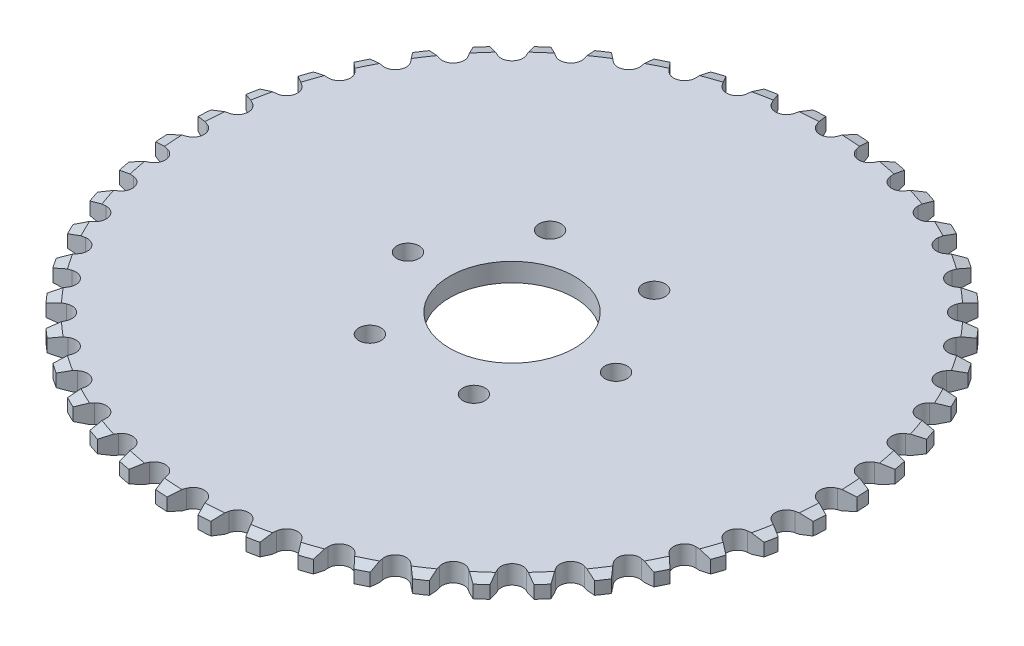
SolidWorks part; units mm, degrees
material "Cast Alloy Steel"
ref_plane "Front Plane" through (0, 0, 0) normal (0, 0, 1) x (1, 0, 0)
ref_plane "Top Plane" through (0, 0, 0) normal (0, 1, 0) x (1, 0, 0)
ref_plane "Right Plane" through (0, 0, 0) normal (1, 0, 0) x (0, 0, -1)
sketch "Sketch1" plane through (0, 0, 0) normal (0, 1, 0) x (1, 0, 0)
  circle A0 centre (0, 0) radius 75.5015
  circle A1 centre (0, 0) radius 14.2812
  dimension "D1" = 151.003
  dimension "D2" = 28.5623
extrude "Boss-Extrude1" add sketch "Sketch1" along normal blind 4.2672
sketch "Sketch2" plane through (0, 4.2672, 0) normal (0, 1, 0) x (1, 0, 0)
  circle A0 centre (0, 0) radius 23.8125 construction
  circle A1 centre (-23.8125, 0) radius 2.54
  circle A2 centre (-11.9063, 20.6222) radius 2.54
  circle A3 centre (11.9062, 20.6222) radius 2.54
  circle A4 centre (23.8125, 0) radius 2.54
  circle A5 centre (11.9063, -20.6222) radius 2.54
  circle A6 centre (-11.9062, -20.6222) radius 2.54
  point P18 (0, 0)
  dimension "D1" = 47.625
  dimension "D2" = 5.08
  dimension "D3" = 6
extrude "Cut-Extrude1" cut sketch "Sketch2" against normal through all
chamfer "Chamfer1" distance 2.54 angle 15 2 edges at (0, 0, 75.5015) (0, 4.2672, 75.5015)
sketch "Sketch3" plane through (0, 4.2672, 0) normal (0, 1, 0) x (1, 0, 0)
  line L0 (0, 75.5015) -> (0, -75.5015) construction
  line L1 (2.363, 72.1269) -> (3.5606, 75.4175)
  line L2 (-2.363, 72.1269) -> (-3.5606, 75.4175)
  line L3 (7.0717, 71.8182) -> (6.3138, 75.237)
  line L4 (11.7572, 71.2014) -> (13.3741, 74.3075)
  line L5 (16.3854, 70.2808) -> (16.0802, 73.7693)
  line L6 (20.9502, 69.0576) -> (22.9588, 71.9261)
  line L7 (25.4187, 67.5408) -> (25.5714, 71.0393)
  line L8 (29.7848, 65.7323) -> (32.1506, 68.3141)
  line L9 (34.0171, 63.6452) -> (34.6251, 67.0938)
  line L10 (38.1098, 61.2822) -> (40.7924, 63.5331)
  line L11 (42.0334, 58.6606) -> (43.0864, 62.0003)
  line L12 (45.7827, 55.7836) -> (48.7361, 57.6651)
  line L13 (49.3305, 52.6722) -> (50.8105, 55.846)
  line L14 (52.6722, 49.3305) -> (55.846, 50.8105)
  line L15 (55.7836, 45.7827) -> (57.6651, 48.7361)
  line L16 (58.6606, 42.0334) -> (62.0003, 43.0864)
  line L17 (61.2822, 38.1098) -> (63.5331, 40.7924)
  line L18 (63.6452, 34.0171) -> (67.0938, 34.6251)
  line L19 (65.7323, 29.7848) -> (68.3141, 32.1506)
  line L20 (67.5408, 25.4187) -> (71.0393, 25.5714)
  line L21 (69.0576, 20.9502) -> (71.9261, 22.9588)
  line L22 (70.2808, 16.3854) -> (73.7693, 16.0802)
  line L23 (71.2014, 11.7572) -> (74.3075, 13.3741)
  line L24 (71.8182, 7.0717) -> (75.237, 6.3138)
  line L25 (72.1269, 2.363) -> (75.4175, 3.5606)
  line L26 (72.1269, -2.363) -> (75.4175, -3.5606)
  line L27 (71.8182, -7.0717) -> (75.237, -6.3138)
  line L28 (71.2014, -11.7572) -> (74.3075, -13.3741)
  line L29 (70.2808, -16.3854) -> (73.7693, -16.0802)
  line L30 (69.0576, -20.9502) -> (71.9261, -22.9588)
  line L31 (67.5408, -25.4187) -> (71.0393, -25.5714)
  line L32 (65.7323, -29.7848) -> (68.3141, -32.1506)
  line L33 (63.6452, -34.0171) -> (67.0938, -34.6251)
  line L34 (61.2822, -38.1098) -> (63.5331, -40.7924)
  line L35 (58.6606, -42.0334) -> (62.0003, -43.0864)
  line L36 (55.7836, -45.7827) -> (57.6651, -48.7361)
  line L37 (52.6722, -49.3305) -> (55.846, -50.8105)
  line L38 (49.3305, -52.6722) -> (50.8105, -55.846)
  line L39 (45.7827, -55.7836) -> (48.7361, -57.6651)
  line L40 (42.0334, -58.6606) -> (43.0864, -62.0003)
  line L41 (38.1098, -61.2822) -> (40.7924, -63.5331)
  line L42 (34.0171, -63.6452) -> (34.6251, -67.0938)
  line L43 (29.7848, -65.7323) -> (32.1506, -68.3141)
  line L44 (25.4187, -67.5408) -> (25.5714, -71.0393)
  line L45 (20.9502, -69.0576) -> (22.9588, -71.9261)
  line L46 (16.3854, -70.2808) -> (16.0802, -73.7693)
  line L47 (11.7572, -71.2014) -> (13.3741, -74.3075)
  line L48 (7.0717, -71.8182) -> (6.3138, -75.237)
  line L49 (2.363, -72.1269) -> (3.5606, -75.4175)
  line L50 (-2.363, -72.1269) -> (-3.5606, -75.4175)
  line L51 (-7.0717, -71.8182) -> (-6.3138, -75.237)
  line L52 (-11.7572, -71.2014) -> (-13.3741, -74.3075)
  line L53 (-16.3854, -70.2808) -> (-16.0802, -73.7693)
  line L54 (-20.9502, -69.0576) -> (-22.9588, -71.9261)
  line L55 (-25.4187, -67.5408) -> (-25.5714, -71.0393)
  line L56 (-29.7848, -65.7323) -> (-32.1506, -68.3141)
  line L57 (-34.0171, -63.6452) -> (-34.6251, -67.0938)
  line L58 (-38.1098, -61.2822) -> (-40.7924, -63.5331)
  line L59 (-42.0334, -58.6606) -> (-43.0864, -62.0003)
  line L60 (-45.7827, -55.7836) -> (-48.7361, -57.6651)
  line L61 (-49.3305, -52.6722) -> (-50.8105, -55.846)
  line L62 (-52.6722, -49.3305) -> (-55.846, -50.8105)
  line L63 (-55.7836, -45.7827) -> (-57.6651, -48.7361)
  line L64 (-58.6606, -42.0334) -> (-62.0003, -43.0864)
  line L65 (-61.2822, -38.1098) -> (-63.5331, -40.7924)
  line L66 (-63.6452, -34.0171) -> (-67.0938, -34.6251)
  line L67 (-65.7323, -29.7848) -> (-68.3141, -32.1506)
  line L68 (-67.5408, -25.4187) -> (-71.0393, -25.5714)
  line L69 (-69.0576, -20.9502) -> (-71.9261, -22.9588)
  line L70 (-70.2808, -16.3854) -> (-73.7693, -16.0802)
  line L71 (-71.2014, -11.7572) -> (-74.3075, -13.3741)
  line L72 (-71.8182, -7.0717) -> (-75.237, -6.3138)
  line L73 (-72.1269, -2.363) -> (-75.4175, -3.5606)
  line L74 (-72.1269, 2.363) -> (-75.4175, 3.5606)
  line L75 (-71.8182, 7.0717) -> (-75.237, 6.3138)
  line L76 (-71.2014, 11.7572) -> (-74.3075, 13.3741)
  line L77 (-70.2808, 16.3854) -> (-73.7693, 16.0802)
  line L78 (-69.0576, 20.9502) -> (-71.9261, 22.9588)
  line L79 (-67.5408, 25.4187) -> (-71.0393, 25.5714)
  line L80 (-65.7323, 29.7848) -> (-68.3141, 32.1506)
  line L81 (-63.6452, 34.0171) -> (-67.0938, 34.6251)
  line L82 (-61.2822, 38.1098) -> (-63.5331, 40.7924)
  line L83 (-58.6606, 42.0334) -> (-62.0003, 43.0864)
  line L84 (-55.7836, 45.7827) -> (-57.6651, 48.7361)
  line L85 (-52.6722, 49.3305) -> (-55.846, 50.8105)
  line L86 (-49.3305, 52.6722) -> (-50.8105, 55.846)
  line L87 (-45.7827, 55.7836) -> (-48.7361, 57.6651)
  line L88 (-42.0334, 58.6606) -> (-43.0864, 62.0003)
  line L89 (-38.1098, 61.2822) -> (-40.7924, 63.5331)
  line L90 (-34.0171, 63.6452) -> (-34.6251, 67.0938)
  line L91 (-29.7848, 65.7323) -> (-32.1506, 68.3141)
  line L92 (-25.4187, 67.5408) -> (-25.5714, 71.0393)
  line L93 (-20.9502, 69.0576) -> (-22.9588, 71.9261)
  line L94 (-16.3854, 70.2808) -> (-16.0802, 73.7693)
  line L95 (-11.7572, 71.2014) -> (-13.3741, 74.3075)
  line L96 (-7.0717, 71.8182) -> (-6.3138, 75.237)
  circle A0 centre (0, 0) radius 72.9869 construction
  circle A1 centre (0, 0) radius 75.5015 construction
  arc A2 (-2.363, 72.1269) -> (2.363, 72.1269) centre (0, 72.9869) ccw
  arc A3 (3.5606, 75.4175) -> (-3.5606, 75.4175) centre (0, 0) ccw
  arc A4 (7.0717, 71.8182) -> (11.7572, 71.2014) centre (9.5267, 72.3625) ccw
  arc A5 (13.3741, 74.3075) -> (6.3138, 75.237) centre (0, 0) ccw
  arc A6 (16.3854, 70.2808) -> (20.9502, 69.0576) centre (18.8904, 70.4999) ccw
  arc A7 (22.9588, 71.9261) -> (16.0802, 73.7693) centre (0, 0) ccw
  arc A8 (25.4187, 67.5408) -> (29.7848, 65.7323) centre (27.9309, 67.4311) ccw
  arc A9 (32.1506, 68.3141) -> (25.5714, 71.0393) centre (0, 0) ccw
  arc A10 (34.0171, 63.6452) -> (38.1098, 61.2822) centre (36.4934, 63.2085) ccw
  arc A11 (40.7924, 63.5331) -> (34.6251, 67.0938) centre (0, 0) ccw
  arc A12 (42.0334, 58.6606) -> (45.7827, 55.7836) centre (44.4316, 57.9044) ccw
  arc A13 (48.7361, 57.6651) -> (43.0864, 62.0003) centre (0, 0) ccw
  arc A14 (49.3305, 52.6722) -> (52.6722, 49.3305) centre (51.6095, 51.6095) ccw
  arc A15 (55.846, 50.8105) -> (50.8105, 55.846) centre (0, 0) ccw
  arc A16 (55.7836, 45.7827) -> (58.6606, 42.0334) centre (57.9044, 44.4316) ccw
  arc A17 (62.0003, 43.0864) -> (57.6651, 48.7361) centre (0, 0) ccw
  arc A18 (61.2822, 38.1098) -> (63.6452, 34.0171) centre (63.2085, 36.4935) ccw
  arc A19 (67.0938, 34.6251) -> (63.5331, 40.7924) centre (0, 0) ccw
  arc A20 (65.7323, 29.7848) -> (67.5408, 25.4187) centre (67.4311, 27.9309) ccw
  arc A21 (71.0393, 25.5714) -> (68.3141, 32.1506) centre (0, 0) ccw
  arc A22 (69.0576, 20.9502) -> (70.2808, 16.3854) centre (70.4999, 18.8904) ccw
  arc A23 (73.7693, 16.0802) -> (71.9261, 22.9588) centre (0, 0) ccw
  arc A24 (71.2014, 11.7572) -> (71.8182, 7.0717) centre (72.3625, 9.5267) ccw
  arc A25 (75.237, 6.3138) -> (74.3075, 13.3741) centre (0, 0) ccw
  arc A26 (72.1269, 2.363) -> (72.1269, -2.363) centre (72.9869, 0) ccw
  arc A27 (75.4175, -3.5606) -> (75.4175, 3.5606) centre (0, 0) ccw
  arc A28 (71.8182, -7.0717) -> (71.2014, -11.7572) centre (72.3625, -9.5267) ccw
  arc A29 (74.3075, -13.3741) -> (75.237, -6.3138) centre (0, 0) ccw
  arc A30 (70.2808, -16.3854) -> (69.0576, -20.9502) centre (70.4999, -18.8904) ccw
  arc A31 (71.9261, -22.9588) -> (73.7693, -16.0802) centre (0, 0) ccw
  arc A32 (67.5408, -25.4187) -> (65.7323, -29.7848) centre (67.4311, -27.9309) ccw
  arc A33 (68.3141, -32.1506) -> (71.0393, -25.5714) centre (0, 0) ccw
  arc A34 (63.6452, -34.0171) -> (61.2822, -38.1098) centre (63.2085, -36.4934) ccw
  arc A35 (63.5331, -40.7924) -> (67.0938, -34.6251) centre (0, 0) ccw
  arc A36 (58.6606, -42.0334) -> (55.7836, -45.7827) centre (57.9044, -44.4316) ccw
  arc A37 (57.6651, -48.7361) -> (62.0003, -43.0864) centre (0, 0) ccw
  arc A38 (52.6722, -49.3305) -> (49.3305, -52.6722) centre (51.6095, -51.6095) ccw
  arc A39 (50.8105, -55.846) -> (55.846, -50.8105) centre (0, 0) ccw
  arc A40 (45.7827, -55.7836) -> (42.0334, -58.6606) centre (44.4316, -57.9044) ccw
  arc A41 (43.0864, -62.0003) -> (48.7361, -57.6651) centre (0, 0) ccw
  arc A42 (38.1098, -61.2822) -> (34.0171, -63.6452) centre (36.4935, -63.2085) ccw
  arc A43 (34.6251, -67.0938) -> (40.7924, -63.5331) centre (0, 0) ccw
  arc A44 (29.7848, -65.7323) -> (25.4187, -67.5408) centre (27.9309, -67.4311) ccw
  arc A45 (25.5714, -71.0393) -> (32.1506, -68.3141) centre (0, 0) ccw
  arc A46 (20.9502, -69.0576) -> (16.3854, -70.2808) centre (18.8904, -70.4999) ccw
  arc A47 (16.0802, -73.7693) -> (22.9588, -71.9261) centre (0, 0) ccw
  arc A48 (11.7572, -71.2014) -> (7.0717, -71.8182) centre (9.5267, -72.3625) ccw
  arc A49 (6.3138, -75.237) -> (13.3741, -74.3075) centre (0, 0) ccw
  arc A50 (2.363, -72.1269) -> (-2.363, -72.1269) centre (0, -72.9869) ccw
  arc A51 (-3.5606, -75.4175) -> (3.5606, -75.4175) centre (0, 0) ccw
  arc A52 (-7.0717, -71.8182) -> (-11.7572, -71.2014) centre (-9.5267, -72.3625) ccw
  arc A53 (-13.3741, -74.3075) -> (-6.3138, -75.237) centre (0, 0) ccw
  arc A54 (-16.3854, -70.2808) -> (-20.9502, -69.0576) centre (-18.8904, -70.4999) ccw
  arc A55 (-22.9588, -71.9261) -> (-16.0802, -73.7693) centre (0, 0) ccw
  arc A56 (-25.4187, -67.5408) -> (-29.7848, -65.7323) centre (-27.9309, -67.4311) ccw
  arc A57 (-32.1506, -68.3141) -> (-25.5714, -71.0393) centre (0, 0) ccw
  arc A58 (-34.0171, -63.6452) -> (-38.1098, -61.2822) centre (-36.4934, -63.2085) ccw
  arc A59 (-40.7924, -63.5331) -> (-34.6251, -67.0938) centre (0, 0) ccw
  arc A60 (-42.0334, -58.6606) -> (-45.7827, -55.7836) centre (-44.4316, -57.9044) ccw
  arc A61 (-48.7361, -57.6651) -> (-43.0864, -62.0003) centre (0, 0) ccw
  arc A62 (-49.3305, -52.6722) -> (-52.6722, -49.3305) centre (-51.6095, -51.6095) ccw
  arc A63 (-55.846, -50.8105) -> (-50.8105, -55.846) centre (0, 0) ccw
  arc A64 (-55.7836, -45.7827) -> (-58.6606, -42.0334) centre (-57.9044, -44.4316) ccw
  arc A65 (-62.0003, -43.0864) -> (-57.6651, -48.7361) centre (0, 0) ccw
  arc A66 (-61.2822, -38.1098) -> (-63.6452, -34.0171) centre (-63.2085, -36.4935) ccw
  arc A67 (-67.0938, -34.6251) -> (-63.5331, -40.7924) centre (0, 0) ccw
  arc A68 (-65.7323, -29.7848) -> (-67.5408, -25.4187) centre (-67.4311, -27.9309) ccw
  arc A69 (-71.0393, -25.5714) -> (-68.3141, -32.1506) centre (0, 0) ccw
  arc A70 (-69.0576, -20.9502) -> (-70.2808, -16.3854) centre (-70.4999, -18.8904) ccw
  arc A71 (-73.7693, -16.0802) -> (-71.9261, -22.9588) centre (0, 0) ccw
  arc A72 (-71.2014, -11.7572) -> (-71.8182, -7.0717) centre (-72.3625, -9.5267) ccw
  arc A73 (-75.237, -6.3138) -> (-74.3075, -13.3741) centre (0, 0) ccw
  arc A74 (-72.1269, -2.363) -> (-72.1269, 2.363) centre (-72.9869, 0) ccw
  arc A75 (-75.4175, 3.5606) -> (-75.4175, -3.5606) centre (0, 0) ccw
  arc A76 (-71.8182, 7.0717) -> (-71.2014, 11.7572) centre (-72.3625, 9.5267) ccw
  arc A77 (-74.3075, 13.3741) -> (-75.237, 6.3138) centre (0, 0) ccw
  arc A78 (-70.2808, 16.3854) -> (-69.0576, 20.9502) centre (-70.4999, 18.8904) ccw
  arc A79 (-71.9261, 22.9588) -> (-73.7693, 16.0802) centre (0, 0) ccw
  arc A80 (-67.5408, 25.4187) -> (-65.7323, 29.7848) centre (-67.4311, 27.9309) ccw
  arc A81 (-68.3141, 32.1506) -> (-71.0393, 25.5714) centre (0, 0) ccw
  arc A82 (-63.6452, 34.0171) -> (-61.2822, 38.1098) centre (-63.2085, 36.4934) ccw
  arc A83 (-63.5331, 40.7924) -> (-67.0938, 34.6251) centre (0, 0) ccw
  arc A84 (-58.6606, 42.0334) -> (-55.7836, 45.7827) centre (-57.9044, 44.4316) ccw
  arc A85 (-57.6651, 48.7361) -> (-62.0003, 43.0864) centre (0, 0) ccw
  arc A86 (-52.6722, 49.3305) -> (-49.3305, 52.6722) centre (-51.6095, 51.6095) ccw
  arc A87 (-50.8105, 55.846) -> (-55.846, 50.8105) centre (0, 0) ccw
  arc A88 (-45.7827, 55.7836) -> (-42.0334, 58.6606) centre (-44.4316, 57.9044) ccw
  arc A89 (-43.0864, 62.0003) -> (-48.7361, 57.6651) centre (0, 0) ccw
  arc A90 (-38.1098, 61.2822) -> (-34.0171, 63.6452) centre (-36.4935, 63.2085) ccw
  arc A91 (-34.6251, 67.0938) -> (-40.7924, 63.5331) centre (0, 0) ccw
  arc A92 (-29.7848, 65.7323) -> (-25.4187, 67.5408) centre (-27.9309, 67.4311) ccw
  arc A93 (-25.5714, 71.0393) -> (-32.1506, 68.3141) centre (0, 0) ccw
  arc A94 (-20.9502, 69.0576) -> (-16.3854, 70.2808) centre (-18.8904, 70.4999) ccw
  arc A95 (-16.0802, 73.7693) -> (-22.9588, 71.9261) centre (0, 0) ccw
  arc A96 (-11.7572, 71.2014) -> (-7.0717, 71.8182) centre (-9.5267, 72.3625) ccw
  arc A97 (-6.3138, 75.237) -> (-13.3741, 74.3075) centre (0, 0) ccw
  point P121 (0, 0)
  dimension "D1" = 145.9738
  dimension "D3" = 2.5146
  dimension "D2" = 20
  dimension "D4" = 48
extrude "Cut-Extrude2" cut sketch "Sketch3" against normal through all
